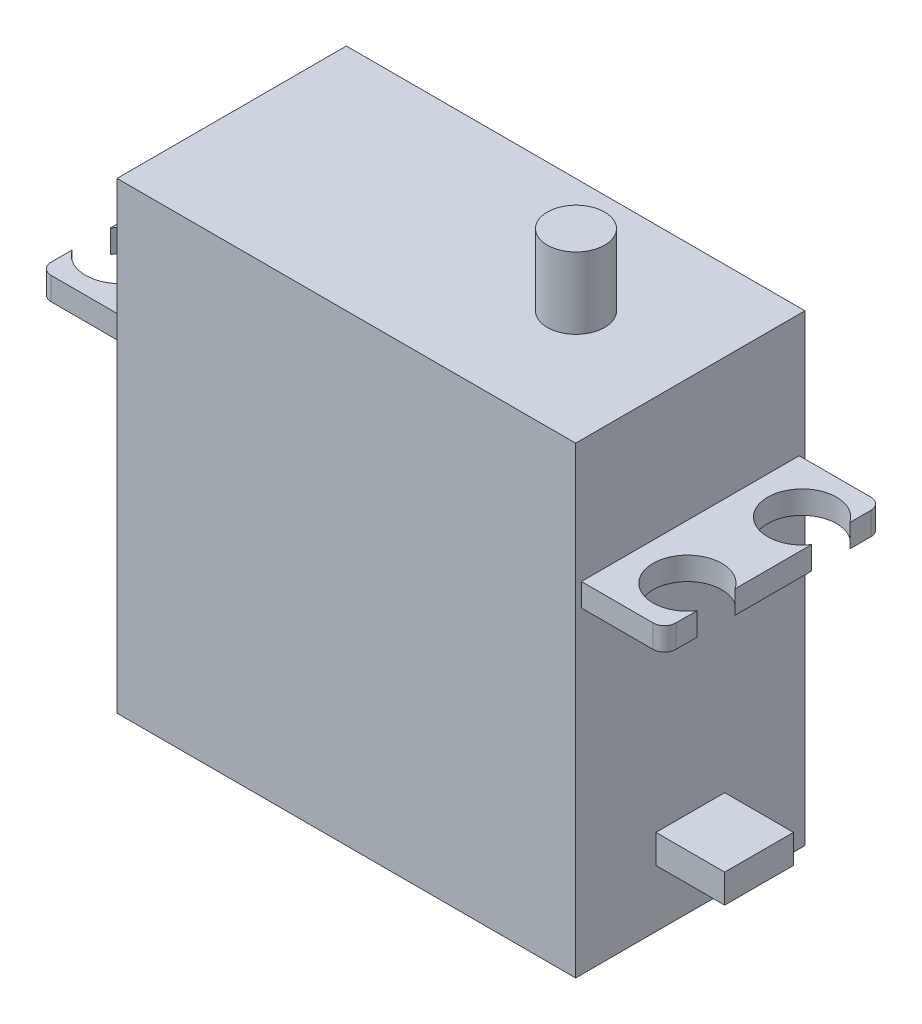
SolidWorks part; units mm, degrees
ref_plane "Front Plane" through (0, 0, 0) normal (0, 0, 1) x (1, 0, 0)
ref_plane "Top Plane" through (0, 0, 0) normal (0, 1, 0) x (1, 0, 0)
ref_plane "Right Plane" through (0, 0, 0) normal (1, 0, 0) x (0, 0, -1)
sketch "Sketch1" plane through (0, 0, 0) normal (0, 0, 1) x (1, 0, 0)
  line L0 (0, 27.7) -> (40, 27.7) construction
  line L1 (0, 0) -> (40, 0)
  line L2 (0, 0) -> (0, 40.4)
  line L3 (0, 40.4) -> (40, 40.4)
  line L4 (40, 0) -> (40, 40.4)
  dimension "D1" = 40
  dimension "D2" = 40.4
  dimension "D3" = 27.7
extrude "Boss-Extrude1" add sketch "Sketch1" along normal blind 20
ref_plane "Plane1" through (0, 27.7, 0) normal (0, -1, 0) x (-1, 0, 0)
sketch "Sketch2" plane through (0, 27.7, 0) normal (0, -1, 0) x (-1, 0, 0)
  line L0 (7.25, -10) -> (0, -10) construction
  line L1 (7.25, -0.5) -> (-47.25, -0.5)
  line L2 (7.25, -0.5) -> (7.25, -19.5)
  line L3 (7.25, -19.5) -> (-47.25, -19.5)
  line L4 (-47.25, -0.5) -> (-47.25, -19.5)
  line L5 (0, -20) -> (0, 0) construction
  line L6 (-20, -20) -> (-20, -19.5) construction
  line L7 (-40, -20) -> (0, -20) construction
  line L8 (-44.75, -10) -> (-47.25, -10) construction
  line L9 (4.75, -5) -> (-44.75, -5) construction
  line L10 (4.75, -5) -> (4.75, -15) construction
  line L11 (4.75, -15) -> (-44.75, -15) construction
  line L12 (-44.75, -5) -> (-44.75, -15) construction
  line L13 (-20, -5) -> (-20, -0.5) construction
  circle A0 centre (4.75, -5) radius 3 construction
  circle A1 centre (4.75, -15) radius 3 construction
  circle A2 centre (-44.75, -15) radius 3 construction
  circle A3 centre (-44.75, -5) radius 3 construction
  dimension "D3" = 10
  dimension "D5" = 6
  dimension "D1" = 54.5
  dimension "D2" = 19
  dimension "D4" = 49.5
extrude "Boss-Extrude2" add sketch "Sketch2" against normal blind 2
sketch "Sketch3" plane through (0, 29.7, 0) normal (0, 1, 0) x (1, 0, 0)
  circle A0 centre (-4.75, -15) radius 3
  circle A1 centre (-4.75, -5) radius 3
  circle A2 centre (44.75, -5) radius 3
  circle A3 centre (44.75, -15) radius 3
  circle A4 centre (44.75, -15) radius 3 construction
  circle A5 centre (44.75, -5) radius 3 construction
  circle A6 centre (-4.75, -5) radius 3 construction
  circle A7 centre (-4.75, -15) radius 3 construction
extrude "Cut-Extrude1" cut sketch "Sketch3" against normal through all
fillet "Fillet1" radius 1 4 edges at (47.25, 28.7, 19.5) (47.25, 28.7, 0.5) (-7.25, 28.7, 0.5) (-7.25, 28.7, 19.5)
sketch "Sketch4" plane through (0, 40.4, 0) normal (0, 1, 0) x (1, 0, 0)
  line L0 (47.25, -0.5) -> (47.25, -19.5) construction
  line L1 (30.03, -10) -> (40, -10) construction
  line L2 (40, -20) -> (40, 0) construction
  circle A0 centre (30.03, -10) radius 2.5
  dimension "D1" = 17.22
  dimension "D2" = 5
extrude "Boss-Extrude3" add sketch "Sketch4" along normal blind 6.223
sketch "Sketch5" plane through (40, 0, 0) normal (1, 0, 0) x (0, 0, -1)
  line L0 (-10, 5) -> (-10, 0) construction
  line L1 (-13, 7.5) -> (-7, 7.5)
  line L2 (-13, 7.5) -> (-13, 5)
  line L3 (-13, 5) -> (-7, 5)
  line L4 (-7, 7.5) -> (-7, 5)
  line L5 (-20, 0) -> (0, 0) construction
  dimension "D1" = 6
  dimension "D2" = 2.5
  dimension "D3" = 5
extrude "Boss-Extrude4" add sketch "Sketch5" along normal blind 6
